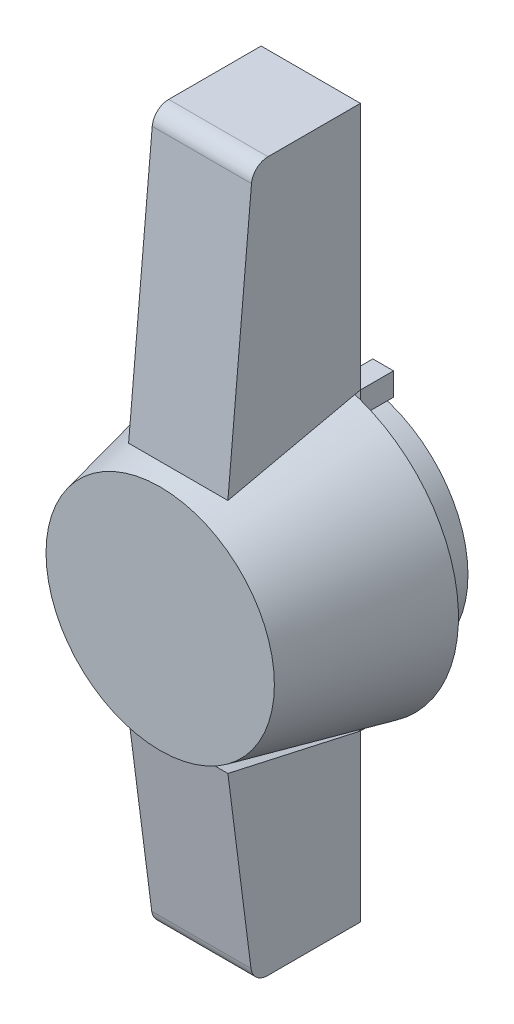
SolidWorks part; units mm, degrees
material "PVC Rígido"
ref_plane "Alzado" through (0, 0, 0) normal (0, 0, 1) x (1, 0, 0)
ref_plane "Planta" through (0, 0, 0) normal (0, 1, 0) x (1, 0, 0)
ref_plane "Vista lateral" through (0, 0, 0) normal (1, 0, 0) x (0, 0, -1)
sketch "Croquis1" plane through (0, 0, 0) normal (0, 0, 1) x (1, 0, 0)
  circle A0 centre (0, 0) radius 14
  dimension "D1" = 28
extrude "Saliente-Extruir1" add sketch "Croquis1" along normal mid plane 5
sketch "Croquis4" plane through (0, 0, 0) normal (0, 1, 0) x (1, 0, 0)
  line L0 (0, -2.5) -> (0, -20.7) construction
  line L1 (-14, -2.5) -> (14, -2.5) construction
  line L2 (0, -2.5) -> (17.85, -2.5)
  line L3 (0, -20.7) -> (13.8, -20.7)
  line L4 (13.8, -20.7) -> (17.85, -2.5)
  line L5 (0, -2.5) -> (0, -20.7)
  dimension "D1" = 18.2
  dimension "D2" = 35.7
  dimension "D3" = 27.6
revolve "Revolución1" add sketch "Croquis4" angle 360 about L0
sketch "Croquis6" plane through (0, 0, 0) normal (1, 0, 0) x (0, 0, -1)
  line L0 (-2.5, 17.85) -> (-2.5, 47.85)
  line L3 (-2.5, 17.85) -> (-20.7, 13.8) construction
  line L4 (-18.52, 14.2851) -> (-2.5, 17.85)
  line L5 (-2.5, 47.85) -> (-15.5, 47.85) construction
  line L6 (-18.52, 14.2851) -> (-15.6638, 46.0292)
  line L7 (-13.6719, 47.85) -> (-2.5, 47.85)
  line L8 (-2.5, -17.85) -> (-18.52, -14.2851)
  line L9 (-20.7, -13.8) -> (-2.5, -17.85) construction
  line L10 (-2.5, -17.85) -> (-2.5, -37.85)
  line L11 (-2.5, -37.85) -> (-15.5, -37.85) construction
  line L12 (-18.52, -14.2851) -> (-15.7237, -36.1042)
  line L13 (-13.74, -37.85) -> (-2.5, -37.85)
  arc A0 (-13.6719, 47.85) -> (-15.6638, 46.0292) centre (-13.6719, 45.85) ccw
  arc A1 (-15.7237, -36.1042) -> (-13.74, -37.85) centre (-13.74, -35.85) ccw
  dimension "D5" = 2
  dimension "D8" = 2
  dimension "D1" = 2.18
  dimension "D2" = 16.02
  dimension "D3" = 30
  dimension "D4" = 13
  dimension "D6" = 16.02
  dimension "D7" = 20
extrude "Saliente-Extruir2" add sketch "Croquis6" along normal mid plane 12 separate body
sketch "Croquis8" plane through (0, 0, 2.5) normal (0, 0, -1) x (-1, 0, 0)
  line L0 (-8.6448, 0) -> (7.3651, 0) construction
  line L1 (-6, 17.85) -> (-3.5, 17.85)
  line L2 (-6, 17.85) -> (-6, 15.0842)
  line L3 (-6, 15.0842) -> (-3.5, 15.0842)
  line L4 (-3.5, 17.85) -> (-3.5, 15.0842)
  line L5 (6, 17.85) -> (3.5, 17.85)
  line L6 (6, 17.85) -> (6, 15.0842)
  line L7 (6, 15.0842) -> (3.5, 15.0842)
  line L8 (3.5, 17.85) -> (3.5, 15.0842)
  line L9 (3.5, -17.85) -> (3.5, -15.0842)
  line L10 (6, -15.0842) -> (3.5, -15.0842)
  line L11 (6, -17.85) -> (6, -15.0842)
  line L12 (6, -17.85) -> (3.5, -17.85)
  line L13 (-3.5, -17.85) -> (-3.5, -15.0842)
  line L14 (-6, -15.0842) -> (-3.5, -15.0842)
  line L15 (-6, -17.85) -> (-6, -15.0842)
  line L16 (-6, -17.85) -> (-3.5, -17.85)
  dimension "D1" = 2.5
  dimension "D2" = 2.5
extrude "Saliente-Extruir4" add sketch "Croquis8" along normal blind 4
